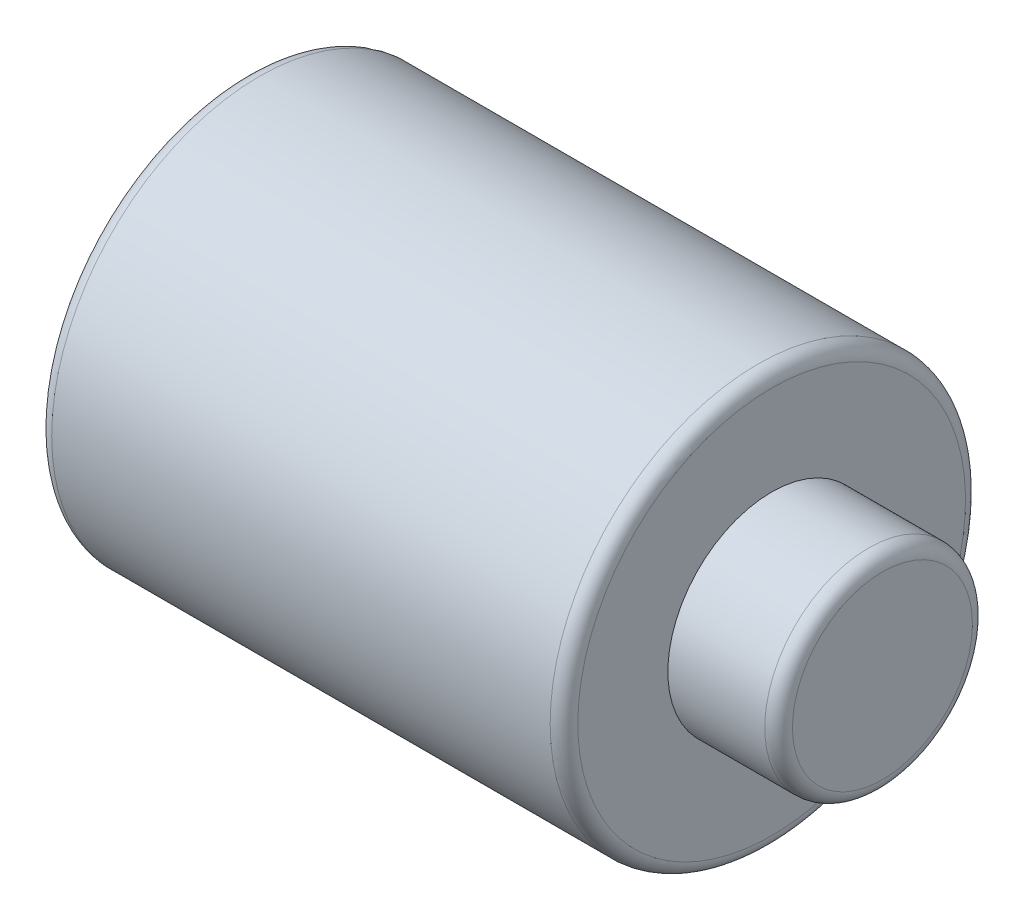
SolidWorks part; units mm, degrees
ref_plane "Ön Düzlem" through (0, 0, 0) normal (0, 0, 1) x (1, 0, 0)
ref_plane "Üst Düzlem" through (0, 0, 0) normal (0, 1, 0) x (1, 0, 0)
ref_plane "Sağ Düzlem" through (0, 0, 0) normal (1, 0, 0) x (0, 0, -1)
sketch "Çizim1" plane through (0, 0, 0) normal (0, 0, 1) x (1, 0, 0)
  line L0 (0, 0) -> (0, 15)
  line L1 (0, 15) -> (38, 15)
  line L2 (38, 15) -> (38, 7.5)
  line L3 (38, 7.5) -> (46, 7.5)
  line L4 (46, 7.5) -> (46, 0)
  line L5 (46, 0) -> (0, 0) construction
  line L6 (0, 0) -> (46, 0)
  dimension "D1" = 15
  dimension "D2" = 7.5
  dimension "D3" = 8
  dimension "D4" = 46
revolve "Döndür1" add sketch "Çizim1" angle 360 about L5
sketch "Çizim2" plane through (0, 0, 0) normal (-1, 0, 0) x (0, 0, 1)
  circle A0 centre (0, 0) radius 4.25
  dimension "D1" = 8.5
extrude "Kes-Ekstrüzyon1" cut sketch "Çizim2" against normal blind 30
cosmetic thread "Kozmetik Diş Açma1" parameters "D2"=10
fillet "Radyus1" radius 1 3 edges at (0, 15, 0) (38, 15, 0) (46, 7.5, 0)
